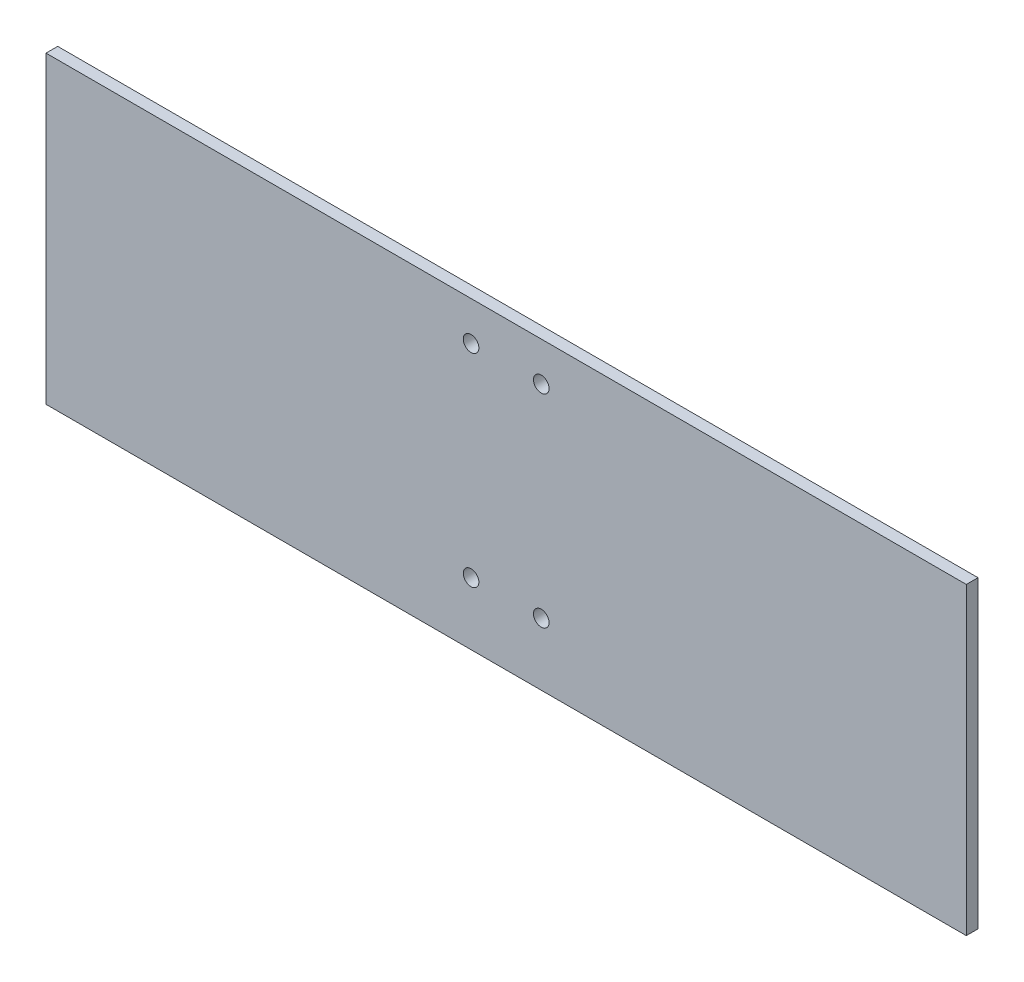
SolidWorks part; units mm, degrees
ref_plane "Plan de face" through (0, 0, 0) normal (0, 0, 1) x (1, 0, 0)
ref_plane "Plan de dessus" through (0, 0, 0) normal (0, 1, 0) x (1, 0, 0)
ref_plane "Plan de droite" through (0, 0, 0) normal (1, 0, 0) x (0, 0, -1)
sketch "Esquisse1" plane through (0, 0, 0) normal (0, 0, 1) x (1, 0, 0)
  line L0 (0, 0) -> (118, 0) construction
  line L1 (0, 0) -> (-118, 0) construction
  line L2 (-118, 0) -> (-118, 33) construction
  line L3 (-118, 33) -> (118, 33)
  line L4 (118, 33) -> (118, -39)
  line L5 (118, -39) -> (-118, -39)
  line L7 (-118, 33) -> (-118, -39)
  dimension "D1" = 39
  dimension "D2" = 118
  dimension "D4" = 72
extrude "Boss.-Extru.1" add sketch "Esquisse1" along normal blind 3
sketch "Esquisse2" plane through (0, 0, 3) normal (0, 0, 1) x (1, 0, 0)
  line L0 (0, -39) -> (0, -29) construction
  line L1 (-118, -39) -> (118, -39) construction
  line L2 (0, -29) -> (9, -29) construction
  line L3 (0, -29) -> (-9, -29) construction
  line L4 (-118, -3) -> (118, -3) construction
  line L5 (-118, 33) -> (-118, -39) construction
  line L6 (118, -39) -> (118, 33) construction
  line L7 (0, 23) -> (-9, 23) construction
  line L8 (0, 23) -> (9, 23) construction
  line L9 (0, 33) -> (0, 23) construction
  circle A0 centre (9, -29) radius 2
  circle A1 centre (-9, -29) radius 2
  circle A2 centre (-9, 23) radius 2
  circle A3 centre (9, 23) radius 2
extrude "Enlèv. mat.-Extru.1" cut sketch "Esquisse2" against normal up to next
sketch "Esquisse3" plane through (0, 0, 3) normal (0, 0, 1) x (1, 0, 0)
  line L0 (-118, -39) -> (-118, -45)
  line L1 (-118, -45) -> (118, -45)
  line L2 (118, -39) -> (118, -45)
  line L4 (118, -39) -> (-118, -39)
extrude "Boss.-Extru.2" add sketch "Esquisse3" against normal blind 3
